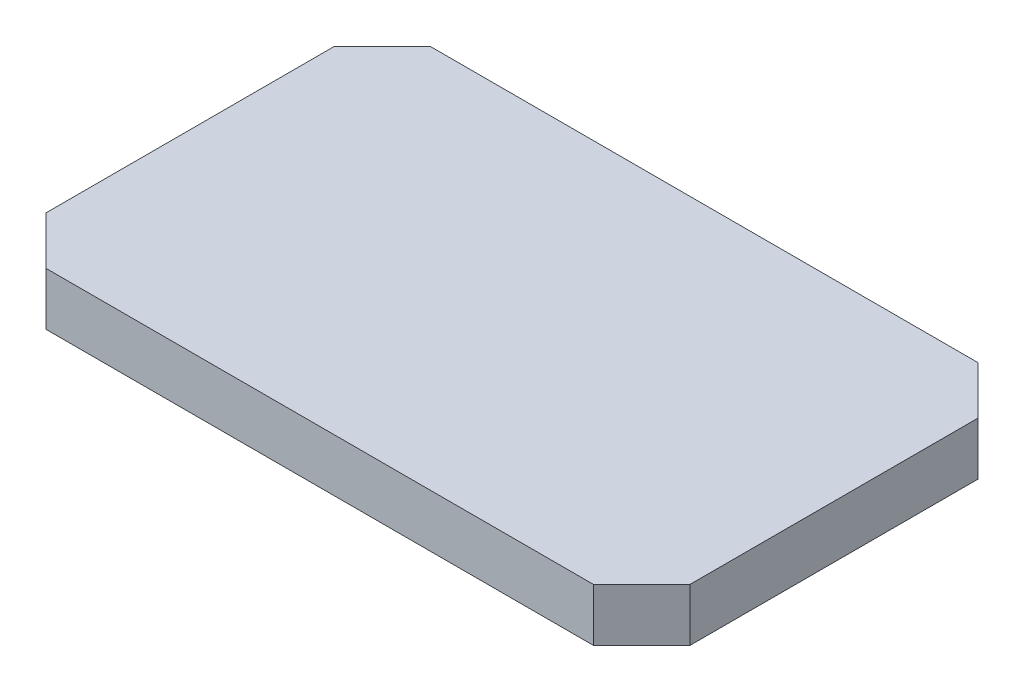
SolidWorks part; units mm, degrees
ref_plane "Front Plane" through (0, 0, 0) normal (0, 0, 1) x (1, 0, 0)
ref_plane "Top Plane" through (0, 0, 0) normal (0, 1, 0) x (1, 0, 0)
ref_plane "Right Plane" through (0, 0, 0) normal (1, 0, 0) x (0, 0, -1)
sketch "Sketch2" plane through (0, 0, 0) normal (0, 1, 0) x (1, 0, 0)
  line L1 (-33.5, 20) -> (33.5, 20)
  line L2 (-33.5, 20) -> (-33.5, -20)
  line L3 (-33.5, -20) -> (33.5, -20)
  line L4 (33.5, 20) -> (33.5, -20)
  line L5 (-33.5, 20) -> (33.5, -20) construction
  line L6 (-33.5, -20) -> (33.5, 20) construction
  point P0 (0, 0)
extrude "Extrude1" add sketch "Sketch2" along normal blind 5.5
chamfer "Chamfer1" distance 5 angle 45 4 edges at (33.5, 2.75, -20) (33.5, 2.75, 20) (-33.5, 2.75, -20) (-33.5, 2.75, 20)
